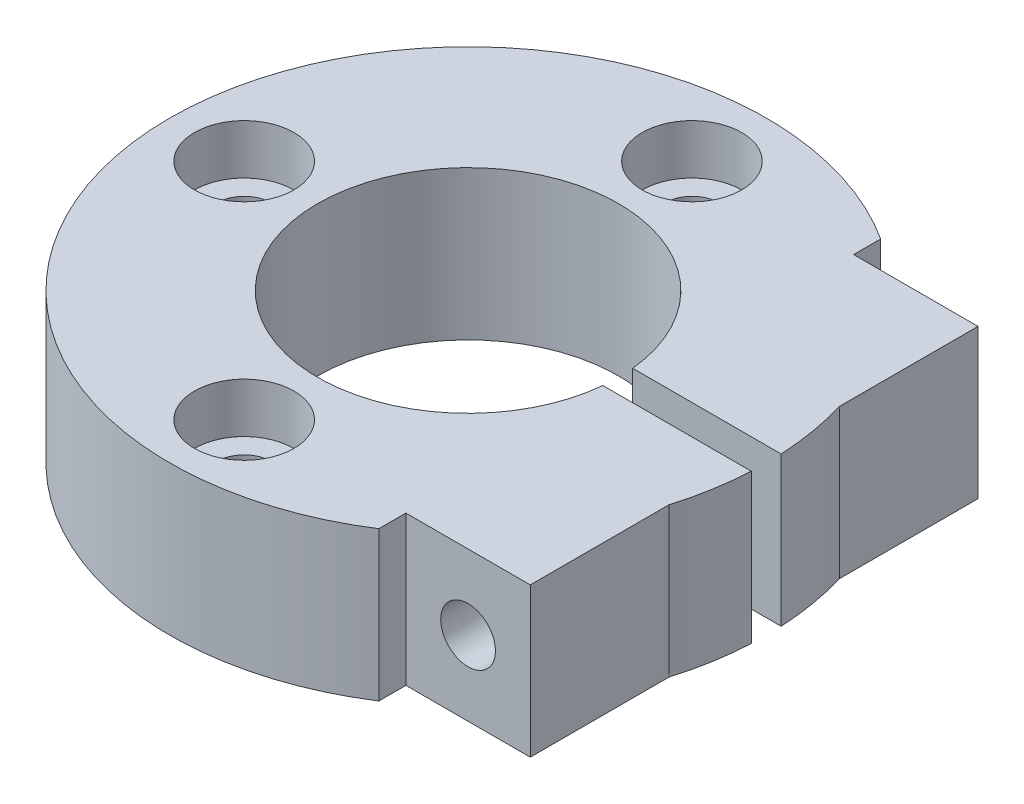
SolidWorks part; units mm, degrees
other "Pivot Shaft Split Clamp Collar"
other "Pivot Shaft Split Clamp Collar Left"
ref_plane "Front Plane" through (0, 0, 0) normal (0, 0, 1) x (1, 0, 0)
ref_plane "Top Plane" through (0, 0, 0) normal (0, 1, 0) x (1, 0, 0)
ref_plane "Right Plane" through (0, 0, 0) normal (1, 0, 0) x (0, 0, -1)
sketch3d "Main Profile Sketch datum points"
  point P0 (0, -157, 0)
  point P1 (10, -157, 0)
  point P2 (0, -157, 10)
ref_plane "Main Profile Sketch plane" through (0, -157, 0) normal (0, -1, 0) x (-1, 0, 0)
sketch "Main Profile Sketch" plane through (0, -157, 0) normal (0, -1, 0) x (-1, 0, 0)
  line L0 (44.7917, -3.4278) -> (44.7917, -9)
  line L1 (44.7917, -9) -> (49.7917, -9)
  line L2 (49.7917, -9) -> (49.7917, -10.0871)
  line L3 (49.7917, 10.0871) -> (49.7917, 9)
  line L4 (44.7917, 9) -> (49.7917, 9)
  line L5 (44.7917, 9) -> (44.7917, 3.4278)
  line L6 (44.3067, 0.6) -> (50.2715, 0.6)
  line L7 (44.3067, -0.6) -> (50.2715, -0.6)
  arc A0 (44.3067, -0.6) -> (44.7917, -3.4278) centre (56.2917, 0) ccw
  arc A1 (49.7917, -10.0871) -> (49.7917, 10.0871) centre (56.2917, 0) ccw
  arc A2 (44.7917, 3.4278) -> (44.3067, 0.6) centre (56.2917, 0) ccw
  arc A3 (50.2715, -0.6) -> (50.2715, 0.6) centre (56.2917, 0) ccw
  circle A4 centre (65.2917, 0) radius 1.1
  circle A5 centre (56.2917, 9) radius 1.1
  circle A6 centre (56.2917, -9) radius 1.1
extrude "Main Extrusion" add sketch "Main Profile Sketch" along normal blind 4 separate body
sketch3d "Detail Profile 2 Sketch datum points"
  point P0 (0, -161, 0)
  point P1 (10, -161, 0)
  point P2 (0, -161, 10)
ref_plane "Detail Profile 2 Sketch plane" through (0, -161, 0) normal (0, -1, 0) x (-1, 0, 0)
sketch "Detail Profile 2 Sketch" plane through (0, -161, 0) normal (0, -1, 0) x (-1, 0, 0)
  line L0 (44.7917, -3.4278) -> (44.7917, -9)
  line L1 (44.7917, -9) -> (49.7917, -9)
  line L2 (49.7917, -9) -> (49.7917, -10.0871)
  line L3 (49.7917, 10.0871) -> (49.7917, 9)
  line L4 (44.7917, 9) -> (49.7917, 9)
  line L5 (44.7917, 9) -> (44.7917, 3.4278)
  line L6 (44.3067, 0.6) -> (50.2715, 0.6)
  line L7 (44.3067, -0.6) -> (50.2715, -0.6)
  arc A0 (44.3067, -0.6) -> (44.7917, -3.4278) centre (56.2917, 0) ccw
  arc A1 (49.7917, -10.0871) -> (49.7917, 10.0871) centre (56.2917, 0) ccw
  arc A2 (44.7917, 3.4278) -> (44.3067, 0.6) centre (56.2917, 0) ccw
  arc A3 (50.2715, -0.6) -> (50.2715, 0.6) centre (56.2917, 0) ccw
  circle A4 centre (65.2917, 0) radius 2
  circle A5 centre (56.2917, 9) radius 2
  circle A6 centre (56.2917, -9) radius 2
extrude "Detail Extrusion 2" add sketch "Detail Profile 2 Sketch" along normal blind 2
sketch3d "Cross Bolt Clearance profile datum points"
  point P0 (-47.2917, -160, -12)
  point P1 (-37.2917, -160, -12)
  point P2 (-47.2917, -150, -12)
ref_plane "Cross Bolt Clearance profile plane" through (0, 0, -12) normal (0, 0, 1) x (1, 0, 0)
sketch "Cross Bolt Clearance profile" plane through (0, 0, -12) normal (0, 0, 1) x (1, 0, 0)
  circle A0 centre (-47.2917, -160) radius 1.1
extrude "Cross Bolt Clearance" cut sketch "Cross Bolt Clearance profile" along normal blind 24
sketch3d "Mirror1 profile datum points"
  point P0 (0, 0, 0)
  point P1 (10, 0, 0)
  point P2 (0, 0, 10)
ref_plane "Mirror1 profile plane" through (0, 0, 0) normal (0, -1, 0) x (-1, 0, 0)
mirror "Mirror1" about plane through (0, 0, 0) normal (0, -1, 0) of bodies 103
delete or keep bodies "Remove1" type delete bodies bodies 103
